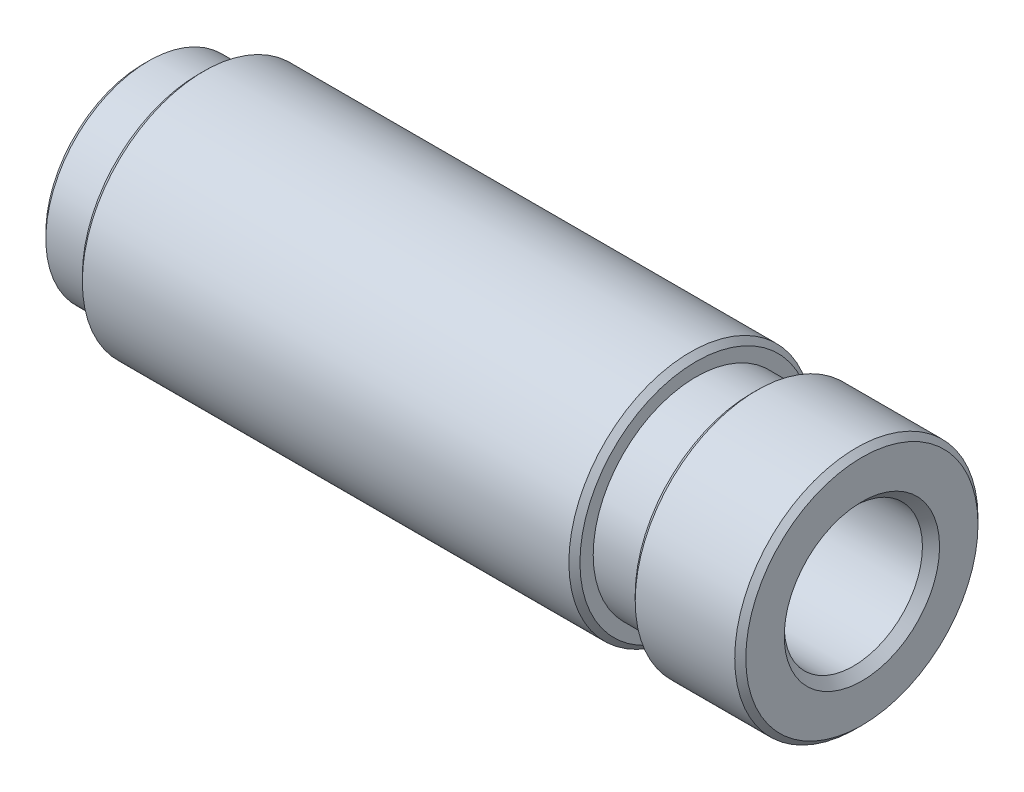
SolidWorks part; units mm, degrees
ref_plane "Plano frontal" through (0, 0, 0) normal (0, 0, 1) x (1, 0, 0)
ref_plane "Plano superior" through (0, 0, 0) normal (0, 1, 0) x (1, 0, 0)
ref_plane "Plano direito" through (0, 0, 0) normal (1, 0, 0) x (0, 0, -1)
sketch "Esboço1" plane through (0, 0, 0) normal (0, 0, 1) x (1, 0, 0)
  line L0 (0, 0) -> (65, 0)
  line L1 (65, 0) -> (65, 11)
  line L2 (65, 11) -> (55, 11)
  line L3 (55, 11) -> (55, 9.3)
  line L4 (55, 9.3) -> (50, 9.3)
  line L5 (50, 9.3) -> (50, 11)
  line L6 (50, 11) -> (5, 11)
  line L7 (5, 11) -> (5, 9.3)
  line L8 (5, 9.3) -> (0, 9.3)
  line L9 (0, 9.3) -> (0, 0)
  point P9 (50, 10.15)
  point P12 (55, 10.15)
  dimension "D1" = 11
  dimension "D2" = 9.3
  dimension "D3" = 9.3
  dimension "D4" = 5
  dimension "D5" = 10
  dimension "D6" = 5
  dimension "D7" = 65
revolve "Revolução1" add sketch "Esboço1" angle 360 about L0
cosmetic thread "Representação de rosca1" parameters "D2"=6.619
cosmetic thread "Representação de rosca4" parameters "D1"=45, "D2"=19.252
hole_wizard "Furo roscado de M14x1.51" positions "Esboço2" profile "Esboço3" tap size "M14x1.5" standard "Ansi Metric"
sketch "Esboço2" plane through (65, 0, 0) normal (1, 0, 0) x (0, 0, -1)
  point P0 (0, 0)
sketch "Esboço3" plane through (65, 0, 0) normal (0, 1, 0) x (0, 0, -1)
  line L0 (0, 0) -> (0, 35.7554)
  line L1 (0, 35.7554) -> (6.25, 32)
  line L2 (6.25, 32) -> (6.25, 0.775)
  line L3 (6.25, 0.775) -> (7.025, 0)
  line L5 (7.025, 0) -> (0, 0)
  line L6 (-6.25, 0.775) -> (-7.025, 0) construction
  line L10 (0, 35.7554) -> (-6.25, 32) construction
  line L11 (0, -6.35) -> (0, 107.95) construction
  dimension "Tap Drill Dia." = 12.5
  dimension "Tap Drill Depth" = 32
  dimension "Near C'Sink Dia." = 14.05
  dimension "Near C'Sink Angle" = 90
  dimension "Drill Angle" = 118
cosmetic thread "Rosca de furo1"
hole_wizard "Furo1" positions "Esboço4" profile "Esboço5" legacy
sketch "Esboço4" plane through (0, 0, 0) normal (-1, 0, 0) x (0, 0, 1)
  point P0 (0, 0)
sketch "Esboço5" plane through (0, 0, 0) normal (0, 1, 0) x (0, 0, 1)
  line L0 (0, 0) -> (0, 33)
  line L1 (0, 33) -> (5.325, 33)
  line L2 (5.325, 33) -> (5.325, 0)
  line L3 (5.325, 0) -> (0, 0)
  line L4 (0, 110) -> (0, -10) construction
  dimension "Diameter" = 10.65
  dimension "Depth" = 33
chamfer "Chanfro1" distance 0.5 angle 45 3 edges at (5, 0, 11) (5, 0, 9.3) (50, 0, 11)
fillet "Filete1" radius 1.2 1 edges at (0, 0, 5.325)
chamfer "Chanfro2" distance 0.5 angle 45 3 edges at (65, 0, 11) (55, 0, 11) (0, 0, 9.3)
